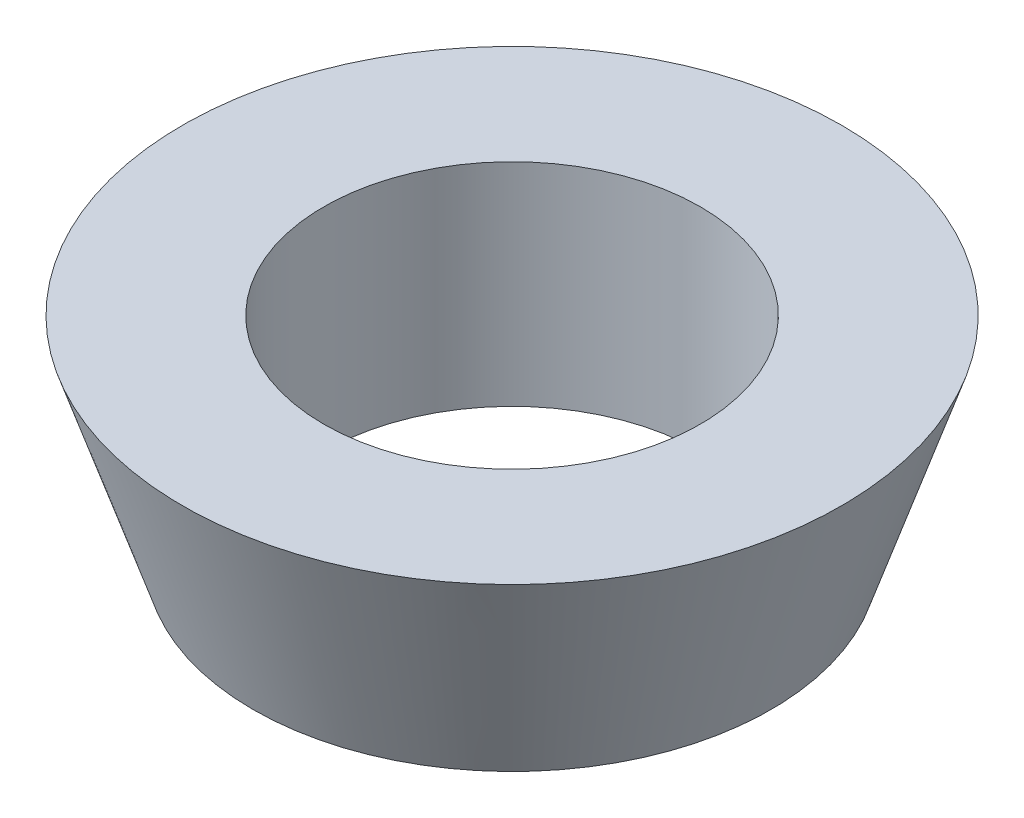
SolidWorks part; units mm, degrees
material "ABS"
ref_plane "Plan de face" through (0, 0, 0) normal (0, 0, 1) x (1, 0, 0)
ref_plane "Plan de dessus" through (0, 0, 0) normal (0, 1, 0) x (1, 0, 0)
ref_plane "Plan de droite" through (0, 0, 0) normal (1, 0, 0) x (0, 0, -1)
sketch "Esquisse1" plane through (0, 0, 0) normal (0, 0, 1) x (1, 0, 0)
  line L0 (0, 0) -> (0, 4.5) construction
  line L2 (4, 4.5) -> (7, 4.5)
  line L3 (7, 4.5) -> (5.5, 0)
  line L4 (5.5, 0) -> (4, 0)
  line L5 (4, 0) -> (4, 4.5)
  dimension "D1" = 8
  dimension "D2" = 11
  dimension "D3" = 14
  dimension "D4" = 4.5
  dimension "D5" = 71.565
  dimension "D6" = 1.5
  dimension "D7" = 1.5
revolve "Révolution1" add sketch "Esquisse1" angle 360 about L0
